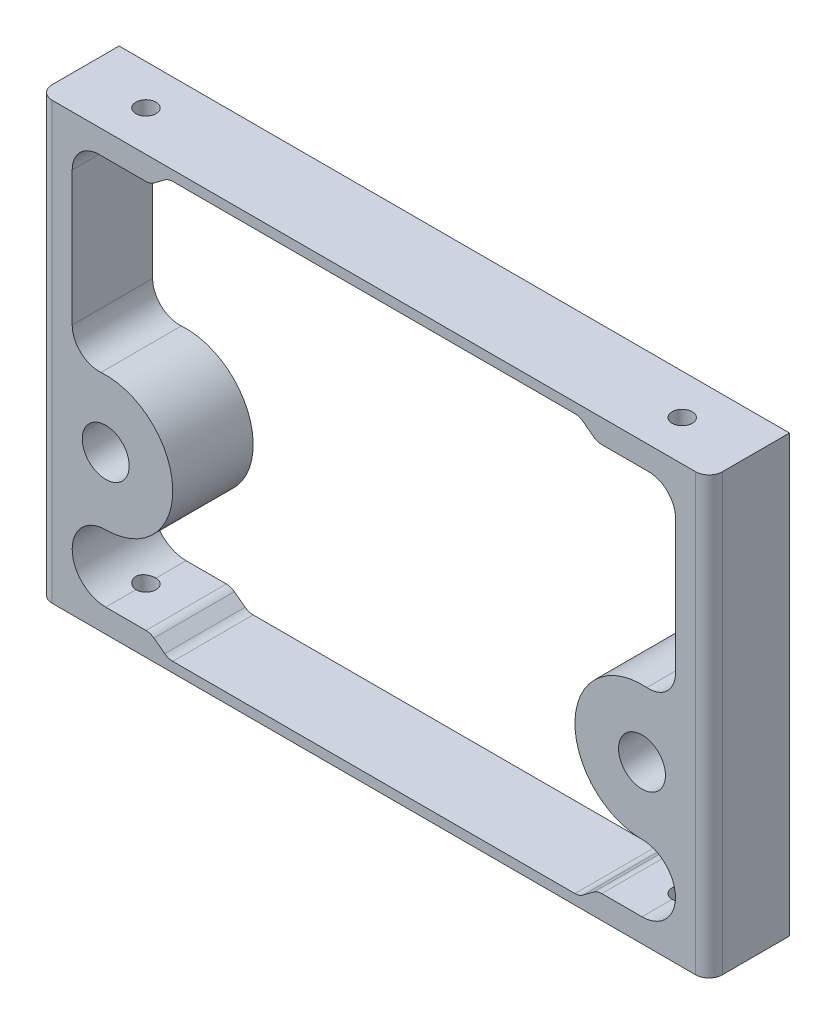
SolidWorks part; units mm, degrees
ref_plane "前视基准面" through (0, 0, 0) normal (0, 0, 1) x (1, 0, 0)
ref_plane "上视基准面" through (0, 0, 0) normal (0, 1, 0) x (1, 0, 0)
ref_plane "右视基准面" through (0, 0, 0) normal (1, 0, 0) x (0, 0, -1)
sketch "草图1" plane through (0, 0, 0) normal (0, 0, 1) x (1, 0, 0)
  line L1 (-50, -32.5) -> (50, -32.5)
  line L2 (-50, -32.5) -> (-50, 32.5)
  line L3 (-50, 32.5) -> (50, 32.5)
  line L4 (50, -32.5) -> (50, 32.5)
  line L5 (-50, -32.5) -> (50, 32.5) construction
  line L6 (-50, 32.5) -> (50, -32.5) construction
  point P0 (0, 0)
  dimension "D1" = 100
  dimension "D2" = 65
extrude "凸台-拉伸1" add sketch "草图1" along normal blind 12
sketch "草图2" plane through (0, 0, 12) normal (0, 0, 1) x (1, 0, 0)
  line L0 (0, 32.5) -> (0, -32.5) construction
  line L1 (50, 32.5) -> (-50, 32.5) construction
  line L2 (-50, -32.5) -> (50, -32.5) construction
  line L3 (30, 31) -> (-30, 31)
  line L4 (-31.2, 30.6) -> (-32.8, 29.4)
  line L5 (-34, 29) -> (-41, 29)
  line L6 (-45, 25) -> (-45, 4.9642)
  line L7 (-40, -29) -> (-34, -29)
  line L8 (-32.8, -29.4) -> (-31.2, -30.6)
  line L9 (-30, -31) -> (30, -31)
  line L10 (-50, 32.5) -> (-50, -32.5) construction
  line L11 (32.8, -29.4) -> (31.2, -30.6)
  line L12 (40, -29) -> (34, -29)
  line L13 (45, 25) -> (45, 4.9642)
  line L14 (34, 29) -> (41, 29)
  line L15 (31.2, 30.6) -> (32.8, 29.4)
  arc A0 (-45, 4.9642) -> (-40.7143, 0.9745) centre (-41, 4.9642) ccw
  arc A1 (-40.7143, 0.9745) -> (-40, -19) centre (-40, -9) cw
  arc A2 (-40, -19) -> (-40, -29) centre (-40, -24) ccw
  arc A3 (-41, 29) -> (-45, 25) centre (-41, 25) ccw
  circle A4 centre (-40, -9) radius 3.5
  circle A5 centre (40, -9) radius 3.5
  arc A6 (41, 29) -> (45, 25) centre (41, 25) cw
  arc A7 (40, -19) -> (40, -29) centre (40, -24) cw
  arc A8 (40.7143, 0.9745) -> (40, -19) centre (40, -9) ccw
  arc A9 (45, 4.9642) -> (40.7143, 0.9745) centre (41, 4.9642) cw
  arc A10 (-34, -29) -> (-32.8, -29.4) centre (-34, -31) cw
  arc A11 (-31.2, -30.6) -> (-30, -31) centre (-30, -29) ccw
  arc A12 (31.2, -30.6) -> (30, -31) centre (30, -29) cw
  arc A13 (32.8, -29.4) -> (34, -29) centre (34, -31) cw
  arc A14 (31.2, 30.6) -> (30, 31) centre (30, 29) ccw
  arc A15 (34, 29) -> (32.8, 29.4) centre (34, 31) cw
  arc A16 (-30, 31) -> (-31.2, 30.6) centre (-30, 29) ccw
  arc A17 (-32.8, 29.4) -> (-34, 29) centre (-34, 31) cw
  point P25 (-45, -24)
  point P27 (-33.3333, -29)
  point P30 (-30.6667, -31)
  point P45 (0, -31)
  point P48 (0, 31)
  point P49 (30.6667, -31)
  point P52 (33.3333, -29)
  point P55 (30.6667, 31)
  point P58 (33.3333, 29)
  point P61 (-30.6667, 31)
  point P64 (-33.3333, 29)
  dimension "D1" = 4
  dimension "D7" = 10
  dimension "D8" = 23.5
  dimension "D11" = 7
  dimension "D12" = 2
  dimension "D2" = 60
  dimension "D3" = 7
  dimension "D4" = 2
  dimension "D5" = 90
  dimension "D6" = 62
  dimension "D9" = 1.5
  dimension "D10" = 3.5
extrude "切除-拉伸1" cut sketch "草图2" against normal through all contours A4 | L0 L3 L4 L5 A3 L6 A0 A1 A2 L7 L8 L9 | L3 L0 L9 L11 L12 A7 A8 A9 L13 A6 L14 L15 | A5
sketch "草图3" plane through (0, 32.5, 0) normal (0, 1, 0) x (1, 0, 0)
  line L0 (50, -12) -> (50, 0) construction
  line L1 (50, -12) -> (-50, -12) construction
  circle A0 centre (40, -6) radius 1.5
  dimension "D1" = 10
  dimension "D2" = 6
  dimension "D3" = 3
extrude "切除-拉伸2" cut sketch "草图3" against normal blind 10
sketch "草图4" plane through (0, -32.5, 0) normal (0, -1, 0) x (1, 0, 0)
  circle A1 centre (40, 6) radius 1.5
  circle A2 centre (40, 6) radius 1.5
  dimension "D1" = 0
extrude "切除-拉伸3" cut sketch "草图4" against normal blind 10
mirror "镜向1" about plane through (0, 0, 0) normal (1, 0, 0) of "切除-拉伸3", "切除-拉伸2"
fillet "圆角1" radius 2 2 edges at (-50, 0, 12) (50, 0, 12)
